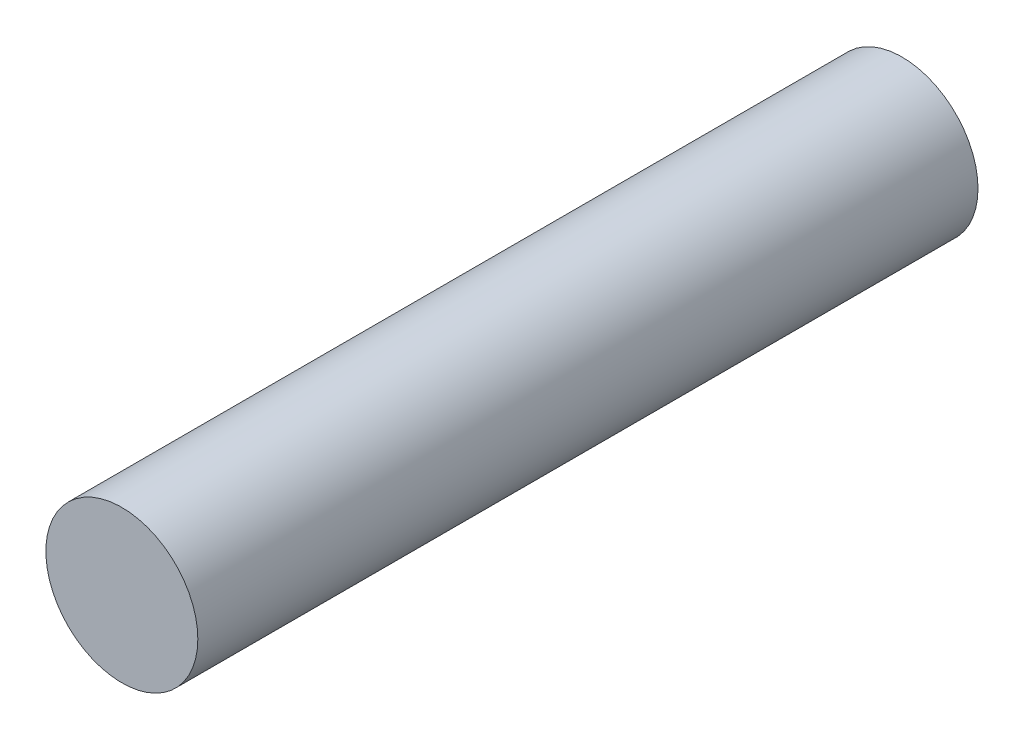
SolidWorks part; units mm, degrees
ref_plane "Front Plane" through (0, 0, 0) normal (0, 0, 1) x (1, 0, 0)
ref_plane "Top Plane" through (0, 0, 0) normal (0, 1, 0) x (1, 0, 0)
ref_plane "Right Plane" through (0, 0, 0) normal (1, 0, 0) x (0, 0, -1)
sketch "Sketch1" plane through (0, 0, 0) normal (0, 0, 1) x (1, 0, 0)
  circle A0 centre (0, 0) radius 0.9525
  dimension "D1" = 1.905
extrude "Boss-Extrude1" add sketch "Sketch1" along normal blind 9.779
